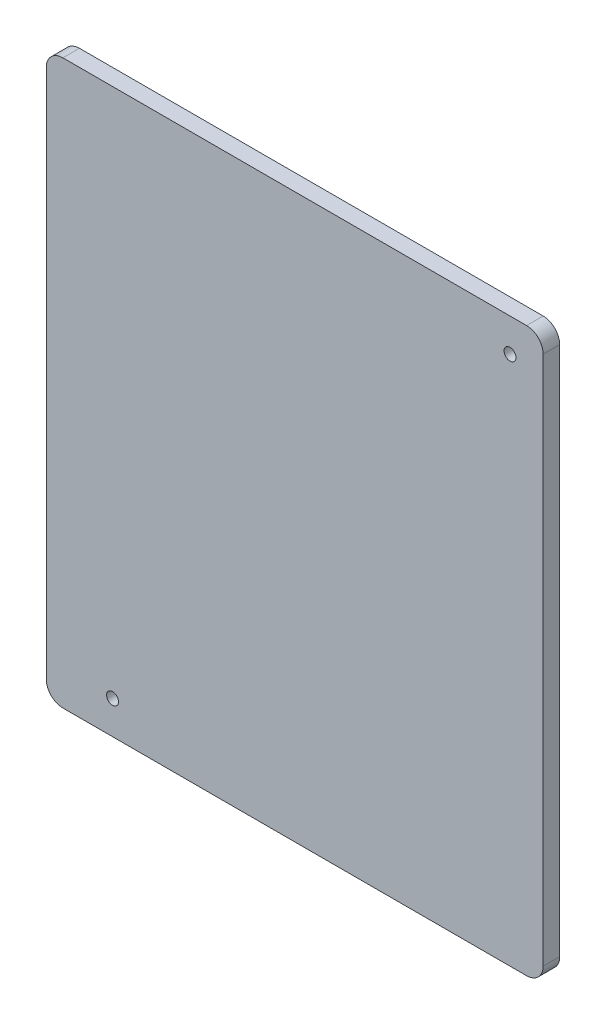
SolidWorks part; units mm, degrees
ref_plane "Plano frontal" through (0, 0, 0) normal (0, 0, 1) x (1, 0, 0)
ref_plane "Plano superior" through (0, 0, 0) normal (0, 1, 0) x (1, 0, 0)
ref_plane "Plano direito" through (0, 0, 0) normal (1, 0, 0) x (0, 0, -1)
sketch "Esboço1" plane through (0, 0, 0) normal (0, 0, 1) x (1, 0, 0)
  line L1 (0, -5) -> (140, -5)
  line L2 (-5, 0) -> (-5, 160)
  line L3 (0, 165) -> (140, 165)
  line L4 (145, 0) -> (145, 160)
  arc A0 (-5, 0) -> (0, -5) centre (0, 0) ccw
  arc A1 (0, 165) -> (-5, 160) centre (0, 160) ccw
  arc A2 (145, 160) -> (140, 165) centre (140, 160) ccw
  arc A3 (140, -5) -> (145, 0) centre (140, 0) ccw
  dimension "D3" = 10
  dimension "D1" = 170
  dimension "D2" = 150
extrude "Ressalto-extrusão1" add sketch "Esboço1" along normal blind 5
sketch "Esboço2" plane through (0, 0, 0) normal (0, 0, -1) x (-1, 0, 0)
  line L0 (-140, 165) -> (0, 165) construction
  line L1 (-135, 155) -> (-15, 155) construction
  line L2 (-135, 155) -> (-135, 5) construction
  line L3 (-135, 5) -> (-15, 5) construction
  line L4 (-15, 155) -> (-15, 5) construction
  line L5 (-145, 0) -> (-145, 160) construction
  dimension "D1" = 120
  dimension "D2" = 150
  dimension "D3" = 10
  dimension "D4" = 10
hole_wizard "Furo com folga de M31" positions "3DSketch1" profile "Esboço3" hole size "M3" standard "ISO"
sketch3d "3DSketch1"
  point P0 (135, 155, 0)
  point P3 (15, 5, 0)
sketch "Esboço3" plane through (135, 155, 0) normal (1, 0, 0) x (0, 1, 0)
  line L0 (0, 0) -> (0, 16.0815)
  line L1 (0, 16.0815) -> (1.8, 15)
  line L2 (1.8, 15) -> (1.8, 0)
  line L5 (1.8, 0) -> (0, 0)
  line L10 (0, 16.0815) -> (-1.8, 15) construction
  line L11 (0, -6.35) -> (0, 107.95) construction
  dimension "Hole Dia." = 3.6
  dimension "Hole Depth" = 15
  dimension "Drill Angle" = 118
